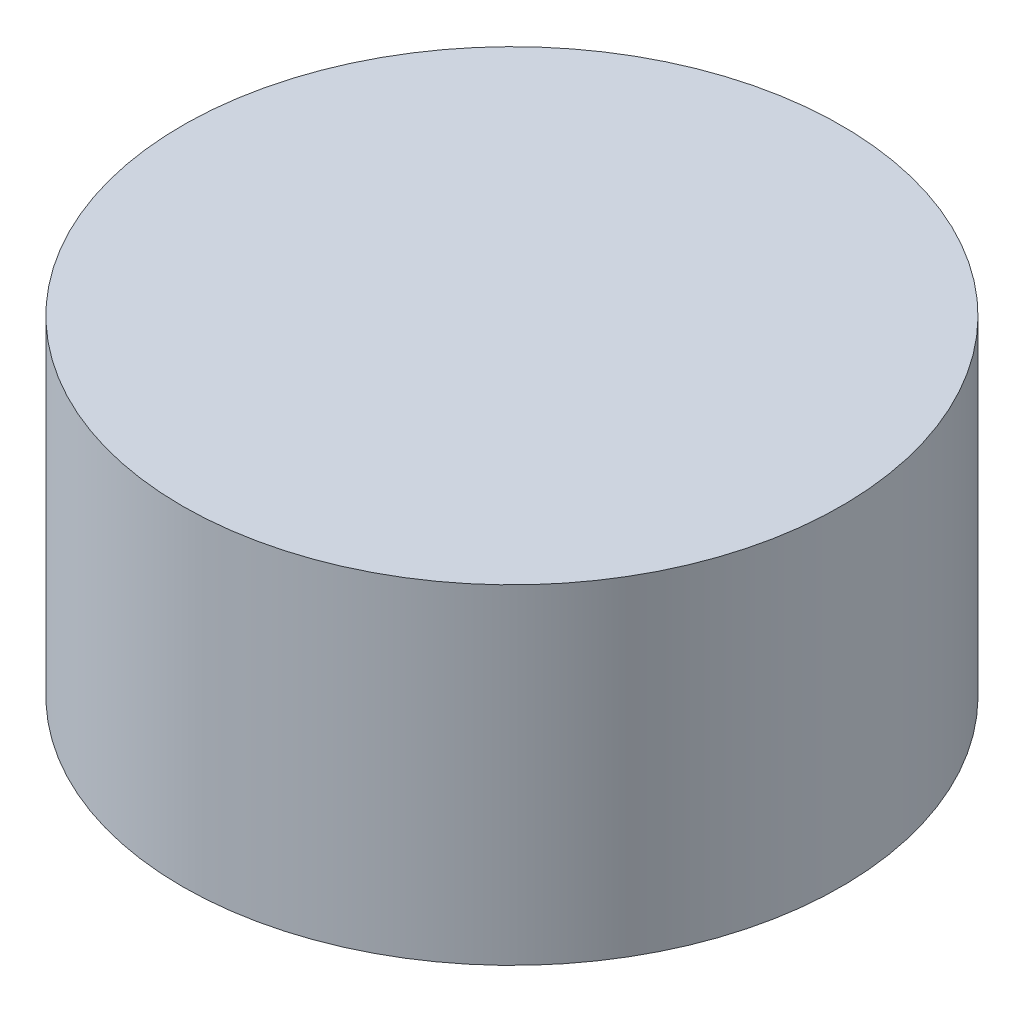
SolidWorks part; units mm, degrees
ref_plane "Front Plane" through (0, 0, 0) normal (0, 0, 1) x (1, 0, 0)
ref_plane "Top Plane" through (0, 0, 0) normal (0, 1, 0) x (1, 0, 0)
ref_plane "Right Plane" through (0, 0, 0) normal (1, 0, 0) x (0, 0, -1)
sketch "Sketch1" plane through (0, 0, 0) normal (0, 1, 0) x (1, 0, 0)
  circle A0 centre (0, 0) radius 3.5
  dimension "D1" = 7
extrude "Boss-Extrude1" add sketch "Sketch1" along normal blind 3.5
